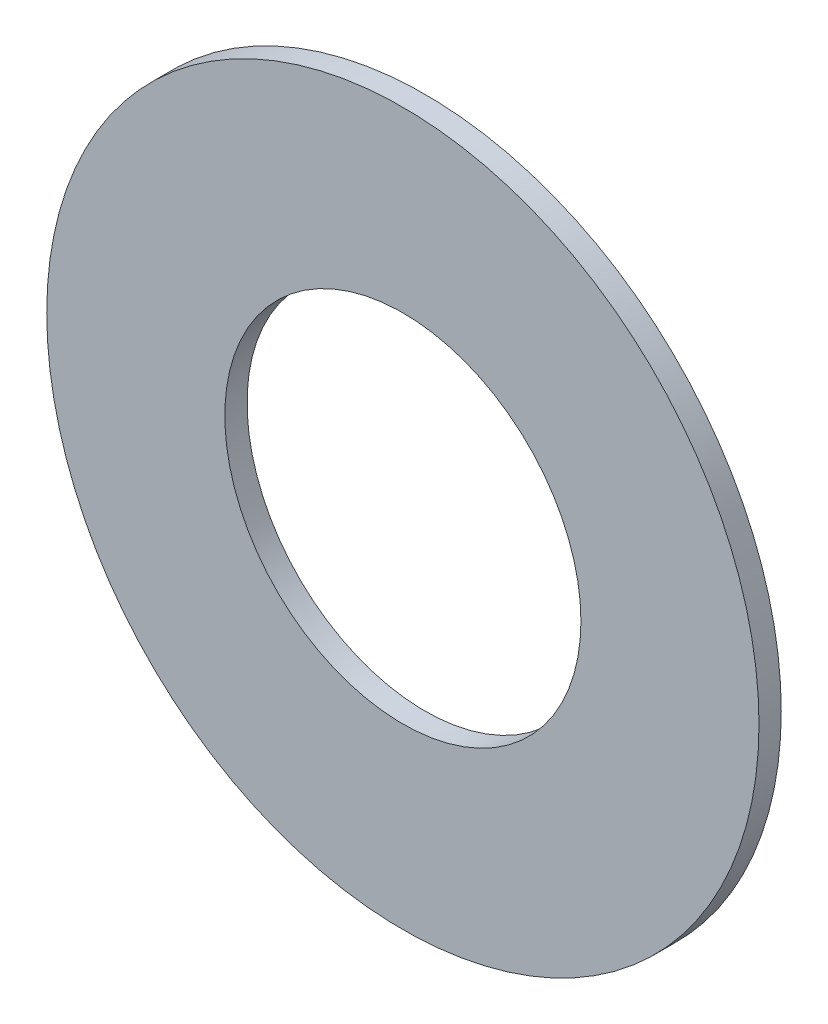
SolidWorks part; units mm, degrees
ref_plane "Front Plane" through (0, 0, 0) normal (0, 0, 1) x (1, 0, 0)
ref_plane "Top Plane" through (0, 0, 0) normal (0, 1, 0) x (1, 0, 0)
ref_plane "Right Plane" through (0, 0, 0) normal (1, 0, 0) x (0, 0, -1)
sketch "Sketch1" plane through (0, 0, 0) normal (0, 0, 1) x (1, 0, 0)
  circle A0 centre (0, 0) radius 4
  circle A1 centre (0, 0) radius 8
  dimension "D1" = 16
  dimension "D2" = 8
extrude "Boss-Extrude1" add sketch "Sketch1" along normal blind 0.5
